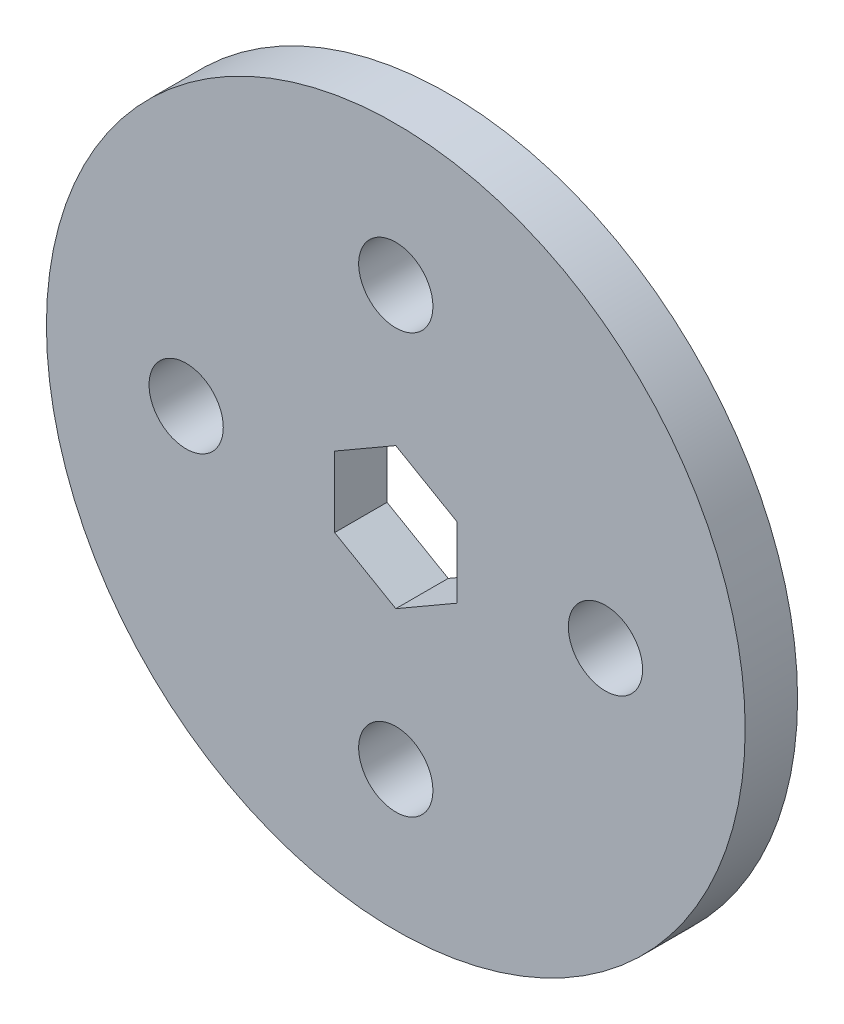
SolidWorks part; units mm, degrees
ref_plane "Front Plane" through (0, 0, 0) normal (0, 0, 1) x (1, 0, 0)
ref_plane "Top Plane" through (0, 0, 0) normal (0, 1, 0) x (1, 0, 0)
ref_plane "Right Plane" through (0, 0, 0) normal (1, 0, 0) x (0, 0, -1)
sketch "Sketch1" plane through (0, 0, 0) normal (0, 0, 1) x (1, 0, 0)
  circle A0 centre (0, 0) radius 20
  dimension "D1" = 40
extrude "Boss-Extrude1" add sketch "Sketch1" along normal blind 3
sketch "Sketch3" plane through (0, 0, 3) normal (0, 0, 1) x (1, 0, 0)
  line L0 (0, 20) -> (0, -20) construction
  line L1 (0, 4.0415) -> (-3.5, 2.0207)
  line L2 (-3.5, 2.0207) -> (-3.5, -2.0207)
  line L3 (-3.5, -2.0207) -> (0, -4.0415)
  line L4 (0, -4.0415) -> (3.5, -2.0207)
  line L5 (3.5, -2.0207) -> (3.5, 2.0207)
  line L6 (3.5, 2.0207) -> (0, 4.0415)
  line L7 (0, 0) -> (0, 4.0415) construction
  circle A0 centre (0, 0) radius 3.5 construction
  circle A1 centre (0, 0) radius 20 construction
  dimension "D1" = 0
  dimension "D2" = 7
extrude "Cut-Extrude2" cut sketch "Sketch3" against normal blind 3
sketch "Sketch4" plane through (0, 0, 3) normal (0, 0, 1) x (1, 0, 0)
  circle A0 centre (0, 12) radius 2.125
  circle A1 centre (12, 0) radius 2.125
  circle A2 centre (0, -12) radius 2.125
  circle A3 centre (-12, 0) radius 2.125
  point P12 (0, 0)
  dimension "D1" = 4.25
  dimension "D2" = 12
  dimension "D3" = 4
extrude "Cut-Extrude3" cut sketch "Sketch4" against normal blind 10
